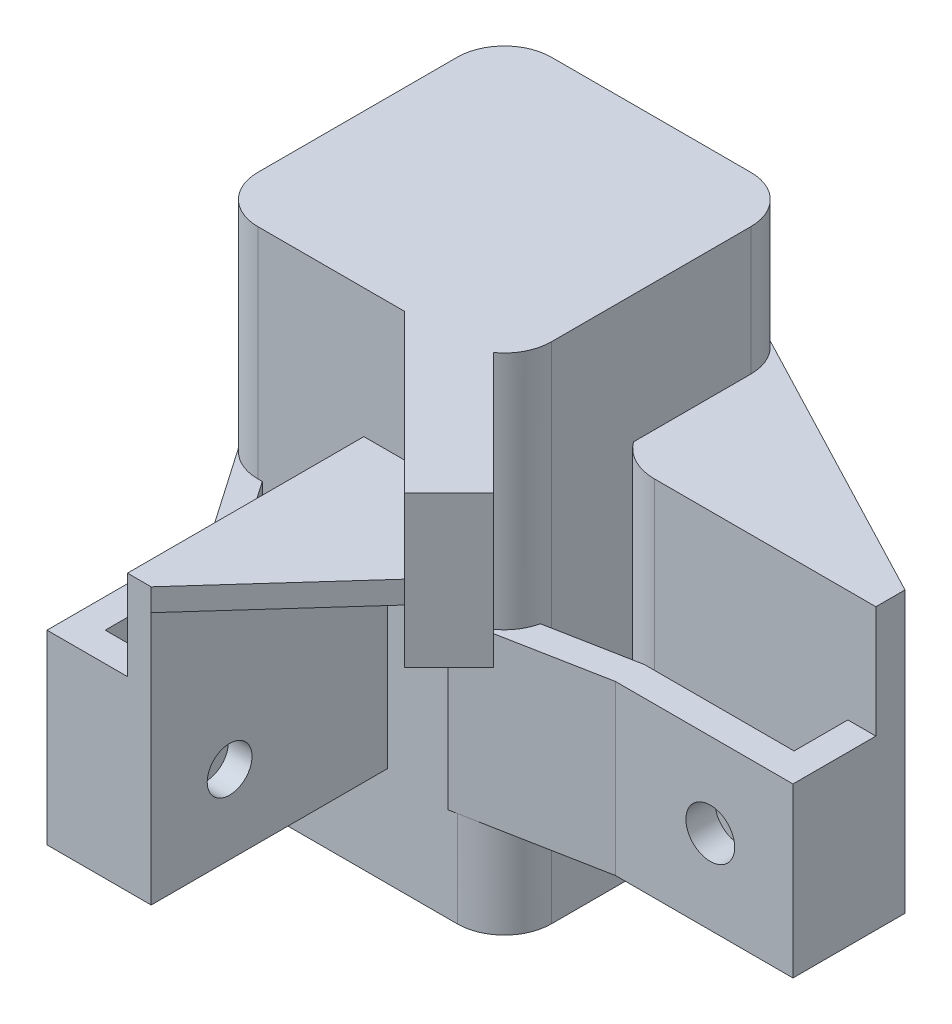
SolidWorks part; units mm, degrees
ref_plane "Front Plane" through (0, 0, 0) normal (0, 0, 1) x (1, 0, 0)
ref_plane "Top Plane" through (0, 0, 0) normal (0, 1, 0) x (1, 0, 0)
ref_plane "Right Plane" through (0, 0, 0) normal (1, 0, 0) x (0, 0, -1)
sketch "Sketch1" plane through (0, 0, 0) normal (0, 1, 0) x (1, 0, 0)
  line L1 (-11.303, -16.637) -> (11.303, -16.637)
  line L2 (-16.637, -11.303) -> (-16.637, 11.303)
  line L3 (-11.303, 16.637) -> (11.303, 16.637)
  line L4 (16.637, -11.303) -> (16.637, 11.303)
  line L5 (-16.637, -16.637) -> (16.637, 16.637) construction
  line L6 (-16.637, 16.637) -> (16.637, -16.637) construction
  arc A0 (-16.637, -11.303) -> (-11.303, -16.637) centre (-11.303, -11.303) ccw
  arc A1 (11.303, -16.637) -> (16.637, -11.303) centre (11.303, -11.303) ccw
  arc A2 (16.637, 11.303) -> (11.303, 16.637) centre (11.303, 11.303) ccw
  arc A3 (-16.637, 11.303) -> (-11.303, 16.637) centre (-11.303, 11.303) cw
  point P0 (0, 0)
  dimension "D3" = 5.334
  dimension "D1" = 33.274
  dimension "D2" = 33.274
extrude "Boss-Extrude1" add sketch "Sketch1" along normal blind 2.54
sketch "Sketch2" plane through (0, 0, 0) normal (0, -1, 0) x (1, 0, 0)
  line L1 (-11.303, 16.637) -> (11.303, 16.637)
  line L2 (-16.637, 11.303) -> (-16.637, -11.303)
  line L3 (-11.303, -16.637) -> (11.303, -16.637)
  line L4 (16.637, 11.303) -> (16.637, -11.303)
  line L5 (-16.637, 16.637) -> (16.637, -16.637) construction
  line L6 (-16.637, -16.637) -> (16.637, 16.637) construction
  line L7 (-14.097, 14.097) -> (14.097, 14.097)
  line L8 (-14.097, 14.097) -> (-14.097, -14.097)
  line L9 (-14.097, -14.097) -> (14.097, -14.097)
  line L10 (14.097, 14.097) -> (14.097, -14.097)
  line L11 (-14.097, 14.097) -> (14.097, -14.097) construction
  line L12 (-14.097, -14.097) -> (14.097, 14.097) construction
  arc A0 (-11.303, 16.637) -> (-16.637, 11.303) centre (-11.303, 11.303) ccw
  arc A1 (-16.637, -11.303) -> (-11.303, -16.637) centre (-11.303, -11.303) ccw
  arc A2 (11.303, -16.637) -> (16.637, -11.303) centre (11.303, -11.303) ccw
  arc A3 (11.303, 16.637) -> (16.637, 11.303) centre (11.303, 11.303) cw
  point P0 (0, 0)
  point P18 (0, 0)
  dimension "D3" = 5.334
  dimension "D1" = 33.274
  dimension "D2" = 33.274
  dimension "D4" = 28.194
extrude "Boss-Extrude2" add sketch "Sketch2" along normal blind 54.61
sketch "Sketch4" plane through (0, 0, -16.637) normal (0, 0, -1) x (-1, 0, 0)
  circle A1 centre (0, -24.13) radius 5.08
extrude "Cut-Extrude2" cut sketch "Sketch4" against normal blind 1.524
sketch "Sketch5" plane through (0, 0, -15.113) normal (0, 0, -1) x (-1, 0, 0)
  circle A0 centre (0, -24.13) radius 2.54
extrude "Cut-Extrude3" cut sketch "Sketch5" against normal blind 1.016
sketch "Sketch6" plane through (0, 2.54, 0) normal (0, 1, 0) x (1, 0, 0)
  line L1 (-11.303, -16.637) -> (11.303, -16.637) construction
  line L2 (5.334, -16.637) -> (23.1688, -34.4718)
  line L4 (23.1688, -34.4718) -> (28.1941, -29.4464)
  line L5 (28.1941, -29.4464) -> (14.3962, -15.6485)
  line L6 (5.334, -16.637) -> (14.3962, -15.6485)
extrude "Boss-Extrude3" add sketch "Sketch6" against normal blind 17.145
sketch "Sketch7" plane through (-0.6262, 0, 0.6262) normal (0.7071, 0, -0.7071) x (-0.7071, 0, -0.7071)
  circle A0 centre (-32.249, -6.0325) radius 2.794
extrude "Cut-Extrude4" cut sketch "Sketch7" against normal up to vertex
sketch "Sketch8" plane through (0, 0, 16.637) normal (0, 0, 1) x (1, 0, 0)
  line L0 (0, 0) -> (0, 2.54)
  line L1 (-11.303, 2.54) -> (5.334, 2.54) construction
  line L2 (0, 2.54) -> (0, -11.938)
ref_plane "Plane1" through (0, -11.938, 0) normal (0, 1, 0) x (1, 0, 0)
sketch "Sketch9" plane through (0, -11.938, 0) normal (0, 1, 0) x (1, 0, 0)
  line L5 (46.5621, -1.143) -> (13.3101, 16.2731)
  line L17 (15.4753, 3.1292) -> (15.4753, 1.4763)
  line L21 (38.2433, -4.445) -> (21.4802, -4.445)
  line L22 (11.303, 16.637) -> (-11.303, 16.637) construction
  line L25 (38.2433, -4.445) -> (46.5621, -4.445)
  line L32 (46.5621, -4.445) -> (46.5621, -1.143)
  line L33 (15.4753, 3.1292) -> (15.4753, 12.1188)
  line L34 (15.4753, 12.1188) -> (12.964, 15.7217)
  line L35 (12.964, 15.7217) -> (13.3101, 16.2731)
  arc A2 (21.4802, -4.445) -> (15.4753, 1.4763) centre (21.4802, 1.5604) cw
  arc A5 (16.637, 11.303) -> (11.303, 16.637) centre (11.303, 11.303) ccw construction
  point P9 (13.2761, -13.462)
  point P10 (29.1224, -11.235)
  point P15 (13.5218, 2.802)
  dimension "D1" = 21.082
  dimension "D2" = 3.302
extrude "Boss-Extrude4" add sketch "Sketch9" against normal blind 2.54
sketch "Sketch10" plane through (0, -14.478, 0) normal (0, -1, 0) x (1, 0, 0)
  line L0 (46.5621, 1.143) -> (46.5621, 4.445)
  line L1 (46.5621, 4.445) -> (21.4802, 4.445)
  line L2 (16.637, -11.303) -> (16.637, 1.9905) construction
  line L3 (46.5621, 1.143) -> (21.9767, 1.143)
  line L4 (16.637, 1.9905) -> (16.637, -2.1142)
  arc A0 (21.4802, 4.445) -> (16.637, 1.9905) centre (21.4802, -1.5604) ccw
  arc A1 (21.9767, 1.143) -> (16.637, -2.1142) centre (21.9767, -4.8624) ccw
extrude "Boss-Extrude5" add sketch "Sketch10" along normal blind 10.16
sketch "Sketch11" plane through (0, -24.638, 0) normal (0, -1, 0) x (1, 0, 0)
  line L0 (21.9767, 1.143) -> (46.5621, 1.143)
  line L1 (46.5621, 1.143) -> (46.5621, 4.445)
  line L2 (43.3871, 4.445) -> (21.4802, 4.445)
  line L3 (16.637, 1.9905) -> (16.637, -2.1142) construction
  line L4 (16.637, 1.9905) -> (16.637, -2.1142)
  line L5 (46.5621, 4.445) -> (46.5621, 13.843)
  line L6 (46.5621, 13.843) -> (26.4323, 13.843)
  line L7 (26.4323, 13.843) -> (10.4983, 16.8872)
  line L8 (10.4983, 16.8872) -> (10.8372, 13.5205)
  line L9 (43.3871, 4.445) -> (43.3871, 10.541)
  line L10 (43.3871, 10.541) -> (26.4323, 10.541)
  line L11 (26.4323, 10.541) -> (10.8372, 13.5205)
  arc A0 (21.4802, 4.445) -> (16.637, 1.9905) centre (21.4802, -1.5604) ccw
  arc A1 (21.9767, 1.143) -> (16.637, -2.1142) centre (21.9767, -4.8624) ccw
  arc A2 (16.637, 11.303) -> (14.3962, 15.6485) centre (11.303, 11.303) ccw construction
  dimension "D1" = 3.175
  dimension "D2" = 12.7
  dimension "D3" = 3.302
extrude "Boss-Extrude6" add sketch "Sketch11" along normal blind 19.05
sketch "Sketch13" plane through (0, 0, 13.843) normal (0, 0, 1) x (1, 0, 0)
  circle A0 centre (37.1895, -34.163) radius 2.7661
extrude "Cut-Extrude5" cut sketch "Sketch13" against normal blind 20.32 and the other way blind 13.716
sketch "Sketch14" plane through (0, -14.605, 0) normal (0, -1, 0) x (1, 0, 0)
  line L3 (3.4049, 43.439) -> (0.715, 43.439)
  line L4 (0.715, 43.439) -> (0.715, 16.637)
  line L5 (11.303, 16.637) -> (10.5235, 16.637) construction
  line L6 (0.715, 16.637) -> (5.334, 16.637)
  line L7 (3.4049, 43.439) -> (21.7796, 23.0319)
  line L8 (28.1941, 29.4464) -> (14.3962, 15.6485) construction
  line L9 (5.334, 16.637) -> (11.303, 16.637)
  line L10 (11.303, 16.637) -> (21.7796, 23.0319)
extrude "Boss-Extrude12" add sketch "Sketch14" against normal blind 2.54
sketch "Sketch15" plane through (0, -14.605, 0) normal (0, -1, 0) x (1, 0, 0)
  line L0 (0.715, 16.637) -> (0.715, 43.439)
  line L1 (0.715, 43.439) -> (3.4049, 43.439)
  line L2 (3.4049, 43.439) -> (3.4049, 16.637)
  line L3 (0.715, 16.637) -> (11.303, 16.637) construction
  line L4 (3.4049, 16.637) -> (0.715, 16.637)
extrude "Boss-Extrude13" add sketch "Sketch15" along normal blind 7.62
sketch "Sketch16" plane through (0, -22.225, 0) normal (0, -1, 0) x (1, 0, 0)
  line L0 (3.4049, 16.637) -> (3.4049, 43.439)
  line L1 (3.4049, 43.439) -> (-8.4068, 43.439)
  line L2 (-8.4068, 43.439) -> (-8.4068, 24.8894)
  line L3 (-8.4068, 24.8894) -> (-15.6929, 14.3329)
  line L4 (3.4049, 16.637) -> (0.715, 16.637)
  line L5 (0.715, 16.637) -> (0.715, 40.137)
  line L6 (0.715, 43.439) -> (0.715, 16.637) construction
  line L7 (0.715, 40.137) -> (-5.1048, 40.137)
  line L8 (-5.1048, 40.137) -> (-5.1048, 24.8894)
  line L9 (-15.6929, 14.3329) -> (-12.3909, 14.3329)
  line L10 (-5.1048, 24.8894) -> (-12.3909, 14.3329)
  arc A0 (-11.303, 16.637) -> (-16.637, 11.303) centre (-11.303, 11.303) ccw construction
  dimension "D1" = 3.302
  dimension "D2" = 3.302
extrude "Boss-Extrude14" add sketch "Sketch16" along normal blind 21.082
sketch "Sketch17" plane through (-8.4068, 0, 0) normal (-1, 0, 0) x (0, 0, 1)
  circle A0 centre (34.549, -34.417) radius 2.54
extrude "Cut-Extrude7" cut sketch "Sketch17" against normal blind 21.082
sketch "Sketch18" plane through (0, -43.688, 0) normal (0, -1, 0) x (1, 0, 0)
  line L0 (14.097, 12.8977) -> (10.8372, 13.5205)
  line L1 (10.8372, 13.5205) -> (10.7792, 14.097)
  line L2 (10.7792, 14.097) -> (14.097, 14.097)
  line L3 (14.097, 14.097) -> (14.097, 12.8977)
extrude "Cut-Extrude8" cut sketch "Sketch18" against normal blind 21.082
